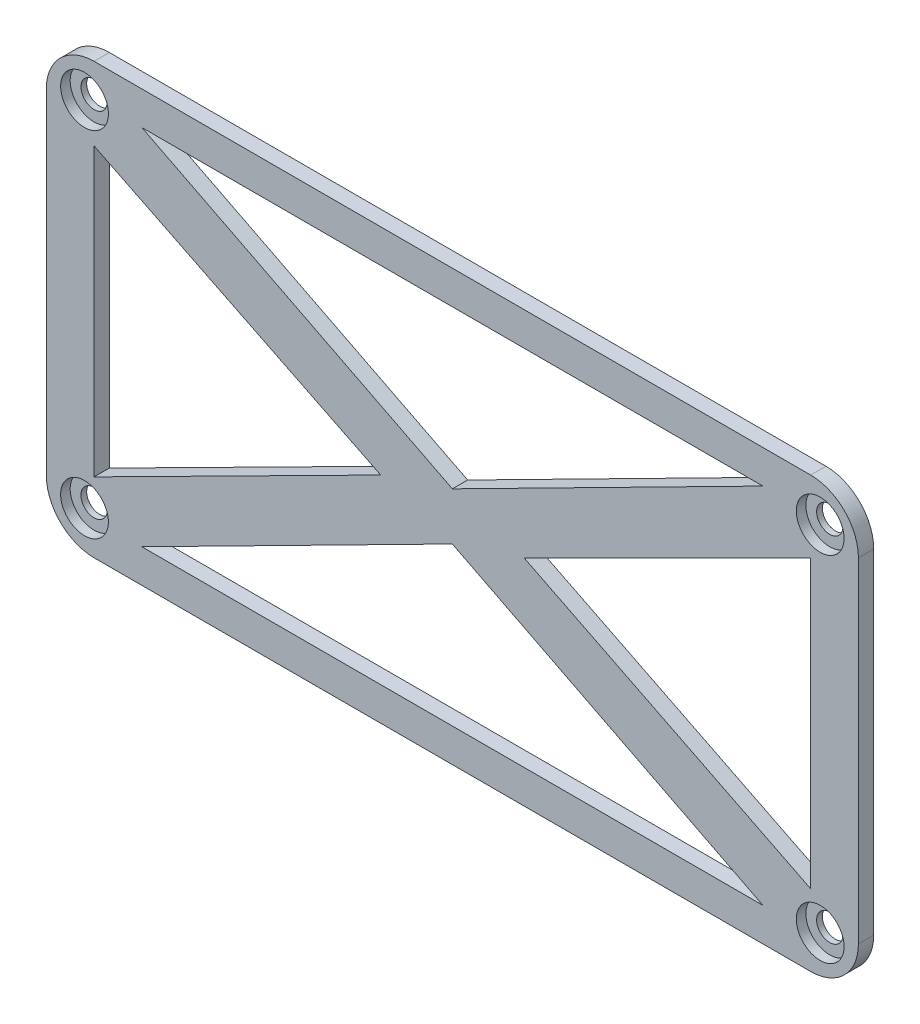
SolidWorks part; units mm, degrees
ref_plane "前视基准面" through (0, 0, 0) normal (0, 0, 1) x (1, 0, 0)
ref_plane "上视基准面" through (0, 0, 0) normal (0, 1, 0) x (1, 0, 0)
ref_plane "右视基准面" through (0, 0, 0) normal (1, 0, 0) x (0, 0, -1)
sketch "草图1" plane through (0, 0, 0) normal (0, 0, 1) x (1, 0, 0)
  line L1 (-72.5741, 45.4874) -> (77.4259, 45.4874)
  line L2 (-82.5741, 35.4874) -> (-82.5741, -34.5126)
  line L3 (-72.5741, -44.5126) -> (77.4259, -44.5126)
  line L4 (87.4259, 35.4874) -> (87.4259, -34.5126)
  arc A0 (-72.5741, 45.4874) -> (-82.5741, 35.4874) centre (-72.5741, 35.4874) ccw
  arc A1 (-72.5741, -44.5126) -> (-82.5741, -34.5126) centre (-72.5741, -34.5126) cw
  arc A2 (87.4259, 35.4874) -> (77.4259, 45.4874) centre (77.4259, 35.4874) ccw
  arc A3 (87.4259, -34.5126) -> (77.4259, -44.5126) centre (77.4259, -34.5126) cw
  dimension "D1" = 10
  dimension "D2" = 10
  dimension "D3" = 10
  dimension "D4" = 10
  dimension "D5" = 90
  dimension "D6" = 170
extrude "凸台-拉伸1" add sketch "草图1" along normal blind 3.2
ref_plane "for screw hole" through (0, 0, 3.2) normal (0, 0, 1) x (1, 0, 0)
sketch "草图2" plane through (0, 0, 3.2) normal (0, 0, 1) x (1, 0, 0)
  line L0 (77.4259, 45.4874) -> (-72.5741, 45.4874) construction
  line L1 (-82.5741, 35.4874) -> (-82.5741, -34.5126) construction
  line L2 (-72.5741, -44.5126) -> (77.4259, -44.5126) construction
  line L3 (87.4259, -34.5126) -> (87.4259, 35.4874) construction
  line L4 (-62.5741, 38.4874) -> (2.4259, 5.4874)
  line L6 (-72.5741, 30.1561) -> (-12.5741, 0.4874)
  line L8 (2.4259, -4.5126) -> (-62.5741, -37.5126)
  line L10 (67.4259, -37.5126) -> (2.4259, -4.5126)
  line L12 (-72.5741, -29.8439) -> (-12.5741, 0.4874)
  line L13 (-72.5741, 30.1561) -> (-72.5741, -29.8439)
  line L15 (-62.5741, -37.5126) -> (67.4259, -37.5126)
  line L17 (67.4259, 38.4874) -> (2.4259, 5.4874)
  line L19 (-62.5741, 38.4874) -> (67.4259, 38.4874)
  line L21 (17.4259, 0.4874) -> (77.4259, 30.4874)
  line L25 (17.4259, 0.4874) -> (77.4259, -29.5126)
  line L26 (77.4259, -29.5126) -> (77.4259, 30.4874)
  circle A0 centre (-74.5741, 37.4874) radius 2.75
  circle A1 centre (-74.5741, -36.5126) radius 2.75
  circle A2 centre (79.4259, 37.4874) radius 2.75
  circle A3 centre (79.4259, -36.5126) radius 2.75
  point P19 (-62.5741, 30.4874)
  point P23 (77.4259, 30.4874)
  point P38 (2.4259, 5.4874)
  point P39 (-12.5741, 0.4874)
  point P40 (67.4259, 38.4874)
  point P41 (-62.5741, 38.4874)
  point P42 (2.4259, -4.5126)
  point P43 (17.4259, 0.4874)
  point P45 (-72.5741, -29.8439)
  point P46 (-62.5741, -37.5126)
  point P47 (67.4259, -37.5126)
  point P48 (77.4259, -29.5126)
  dimension "D2" = 5.5
  dimension "D3" = 5.5
  dimension "D4" = 5.5
  dimension "D8" = 8
  dimension "D9" = 8
  dimension "D10" = 8
  dimension "D11" = 5.5
  dimension "D14" = 70
  dimension "D5" = 8
  dimension "D6" = 8
  dimension "D7" = 8
  dimension "D12" = 8
  dimension "D13" = 8
  dimension "D15" = 70
  dimension "D16" = 40
  dimension "D17" = 45
  dimension "D18" = 45
  dimension "D19" = 60
  dimension "D20" = 7
  dimension "D21" = 7
  dimension "D22" = 20
  dimension "D23" = 20
  dimension "D24" = 20
  dimension "D25" = 10
  dimension "D26" = 7
  dimension "D27" = 20
  dimension "D28" = 15
  dimension "D29" = 15
  dimension "D30" = 10
  dimension "D31" = 10
  dimension "D32" = 15
  dimension "D33" = 7
  dimension "D34" = 20
extrude "切除-拉伸1" cut sketch "草图2" against normal blind 10 and the other way blind 39
ref_plane "for outer screw hole" through (0, 0, 3.2) normal (0, 0, 1) x (1, 0, 0)
sketch "草图3" plane through (0, 0, 3.2) normal (0, 0, 1) x (1, 0, 0)
  circle A0 centre (-74.5741, 37.4874) radius 5
  circle A1 centre (79.4259, 37.4874) radius 5
  circle A2 centre (79.4259, -36.5126) radius 5
  circle A3 centre (-74.5741, -36.5126) radius 5
  dimension "D1" = 10
  dimension "D2" = 10
  dimension "D3" = 10
  dimension "D4" = 10
extrude "切除-拉伸2" cut sketch "草图3" against normal blind 2
ref_plane "for stands" through (0, 0, 3.2) normal (0, 0, 1) x (1, 0, 0)
